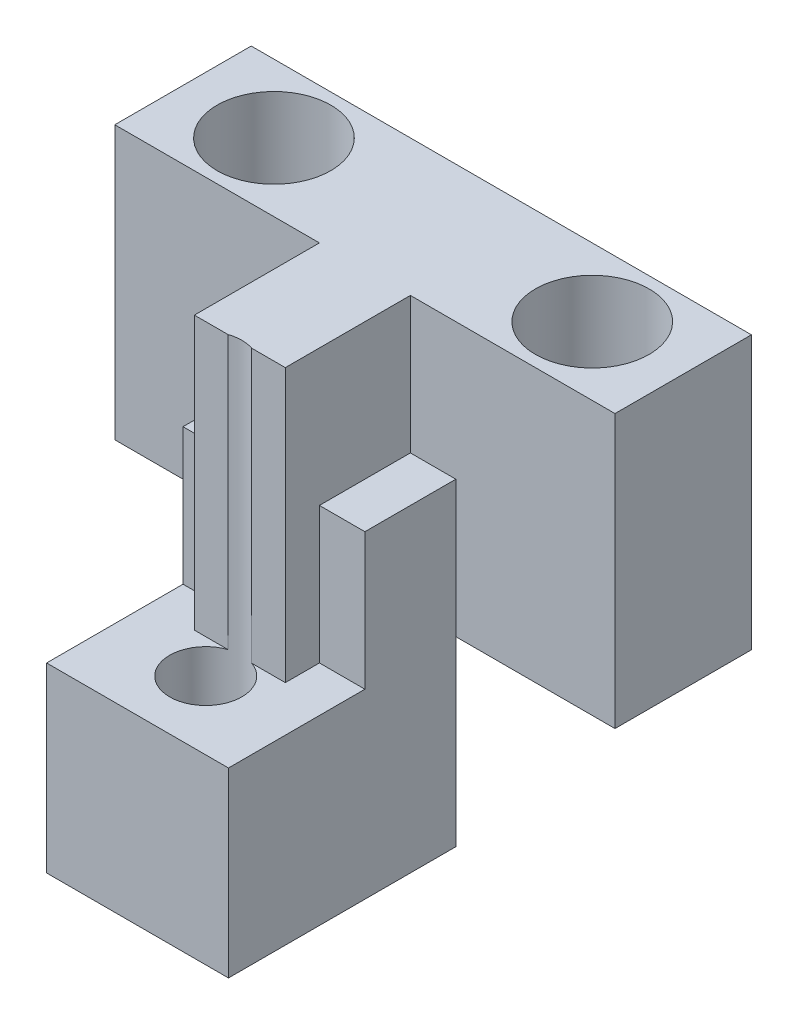
SolidWorks part; units mm, degrees
material "7075-T6 (SN)"
ref_plane "Front Plane" through (0, 0, 0) normal (0, 0, 1) x (1, 0, 0)
ref_plane "Top Plane" through (0, 0, 0) normal (0, 1, 0) x (1, 0, 0)
ref_plane "Right Plane" through (0, 0, 0) normal (1, 0, 0) x (0, 0, -1)
sketch "Sketch1" plane through (0, 0, 0) normal (0, 0, 1) x (1, 0, 0)
  line L1 (-22, -12) -> (22, -12)
  line L2 (-22, -12) -> (-22, 12)
  line L3 (-22, 12) -> (22, 12)
  line L4 (22, -12) -> (22, 12)
extrude "Crosshead_Base" add sketch "Sketch1" along normal blind 12
sketch "Sketch2" plane through (0, 0, 0) normal (0, 0, 1) x (1, 0, 0)
  line L1 (-4, -12) -> (4, -12)
  line L2 (-4, -12) -> (-4, 12)
  line L3 (-4, 12) -> (4, 12)
  line L4 (4, -12) -> (4, 12)
extrude "Shoe_Upriser" add sketch "Sketch2" along normal blind 11 from offset 12
sketch "Sketch3" plane through (0, 0, 0) normal (0, 0, 1) x (1, 0, 0)
  line L1 (-8, -28) -> (8, -28)
  line L2 (-8, -28) -> (-8, 0)
  line L3 (-8, 0) -> (8, 0)
  line L4 (8, -28) -> (8, 0)
extrude "Adapter_Bridge" add sketch "Sketch3" along normal blind 8 from offset 12
sketch "Sketch4" plane through (0, 0, 0) normal (0, 0, 1) x (1, 0, 0)
  line L1 (-8, -28) -> (8, -28)
  line L2 (-8, -28) -> (-8, -12)
  line L3 (-8, -12) -> (8, -12)
  line L4 (8, -28) -> (8, -12)
extrude "Threaded_Rod_Adapter" add sketch "Sketch4" along normal blind 12 from offset 20
sketch "Sketch5" plane through (0, 0, 0) normal (0, 1, 0) x (1, 0, 0)
  circle A0 centre (-14, -6) radius 5
  circle A1 centre (14, -6) radius 5
extrude "Two_Bronze_Bush_Housings" cut sketch "Sketch5" against normal through all and the other way through all
sketch "Sketch6" plane through (0, 0, 0) normal (0, 1, 0) x (1, 0, 0)
  circle A0 centre (0, -26) radius 3.175
extrude "Quarter20_Adapter_Major_Envelope" cut sketch "Sketch6" against normal through all and the other way through all
